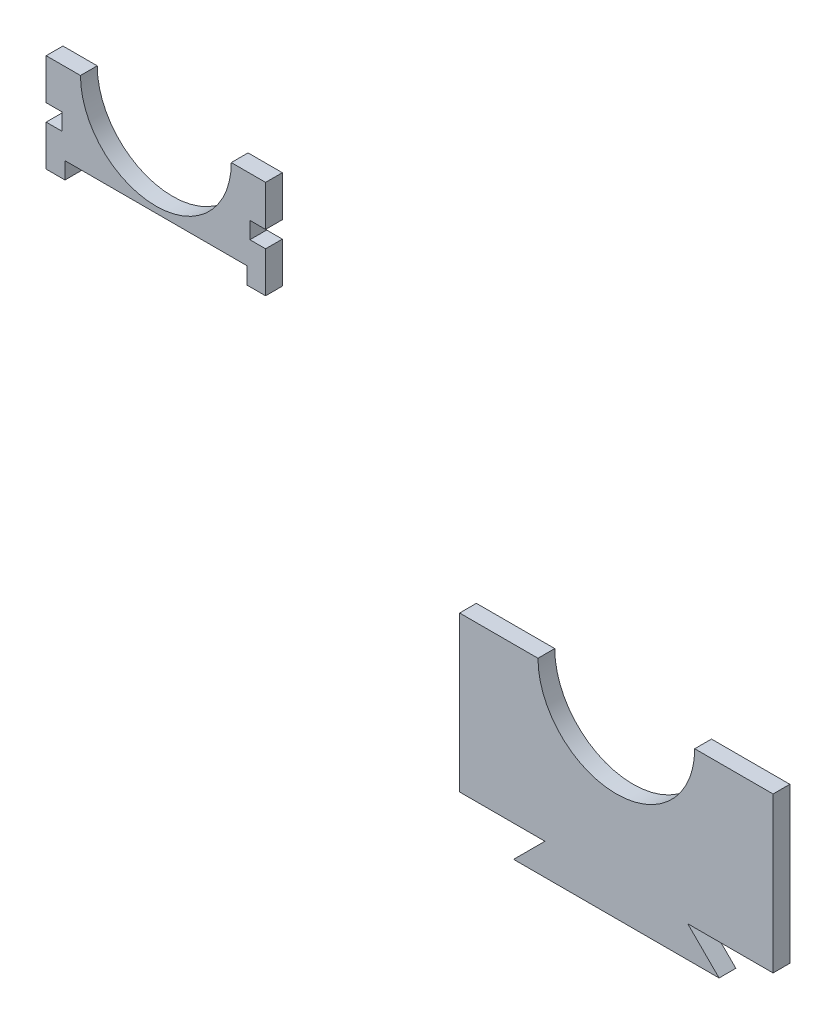
SolidWorks part; units mm, degrees
ref_plane "Front Plane" through (0, 0, 0) normal (0, 0, 1) x (1, 0, 0)
ref_plane "Top Plane" through (0, 0, 0) normal (0, 1, 0) x (1, 0, 0)
ref_plane "Right Plane" through (0, 0, 0) normal (1, 0, 0) x (0, 0, -1)
sketch "Model" plane through (0, 0, 0) normal (0, 0, 1) x (1, 0, 0)
  line L0 (-35, 13) -> (-35, 26)
  line L1 (-29, 0) -> (29, 0)
  line L2 (-35, -5.3175) -> (-35, 7.65)
  line L3 (-35, 26) -> (-24.055, 26)
  line L4 (35, -5.3175) -> (35, 7.65)
  line L5 (-35, 13) -> (-30, 13)
  line L6 (35, -5.3175) -> (35, -5.35)
  line L7 (35, -5.35) -> (29, -5.35)
  line L8 (29, 0) -> (29, -5.35)
  line L9 (0, 0) -> (0, 26) construction
  line L10 (-35, -5.3175) -> (-35, -5.35)
  line L11 (-35, -5.35) -> (-29, -5.35)
  line L12 (-29, 0) -> (-29, -5.35)
  line L13 (-35, 7.65) -> (-30, 7.65)
  line L14 (-30, 13) -> (-30, 7.65)
  line L15 (30, 13) -> (30, 7.65)
  line L16 (35, 7.65) -> (30, 7.65)
  line L17 (35, 13) -> (30, 13)
  line L18 (35, 13) -> (35, 26)
  line L19 (24.055, 26) -> (35, 26)
  line L20 (96.8971, -111.4772) -> (124.1195, -111.4772)
  line L21 (114.1195, -121.4772) -> (179.6748, -121.4772)
  line L22 (96.8971, -111.4772) -> (96.8971, -62.0227)
  line L23 (96.8971, -62.0227) -> (121.8971, -62.0227)
  line L24 (196.8971, -111.4772) -> (196.8971, -62.0227)
  line L25 (114.1195, -121.4772) -> (124.1195, -111.4772)
  line L26 (146.8971, -121.4772) -> (146.8971, -62.0227) construction
  line L27 (179.6748, -121.4772) -> (169.6748, -111.4772)
  line L28 (169.6748, -111.4772) -> (196.8971, -111.4772)
  line L29 (171.8971, -62.0227) -> (196.8971, -62.0227)
  line L40 (-35, 26) -> (35, 26) construction
  arc A0 (-24.055, 26) -> (24.055, 26) centre (0, 26) ccw
  arc A1 (121.8971, -62.0227) -> (171.8971, -62.0227) centre (146.8971, -62.0227) ccw
  dimension "D16" = 24.055
  dimension "D10" = 50
  dimension "D8" = 58
  dimension "D2" = 70
  dimension "D4" = 26
  dimension "D6" = 5.35
  dimension "D9" = 5.35
  dimension "D11" = 5
  dimension "D14" = 13
  dimension "D3" = 100
  dimension "D5" = 65.5553
  dimension "D7" = 45
  dimension "D12" = 10
extrude "Boss-Extrude1" add sketch "Model" along normal blind 5.35
equation "\"mdfthick\"= 5.35"
equation "\"D6@Model\"=\"mdfthick\""
equation "\"D9@Model\"=\"mdfthick\""
equation "\"D1@Boss-Extrude1\"=\"mdfthick\""
